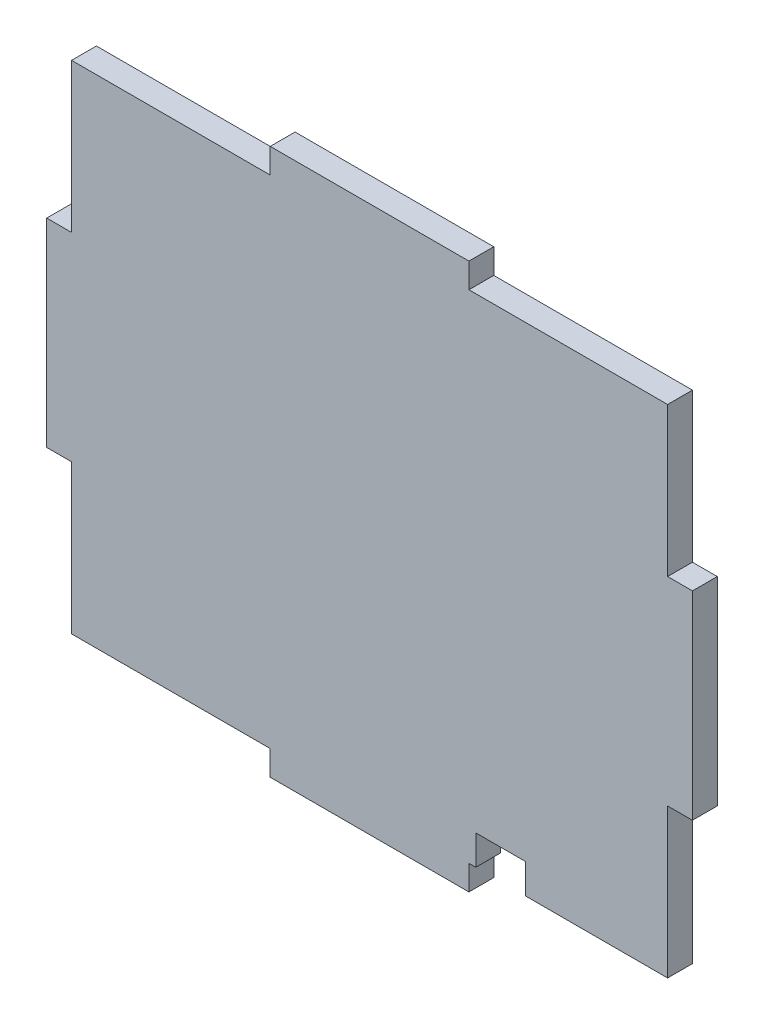
SolidWorks part; units mm, degrees
material "Maple"
ref_plane "Front Plane" through (0, 0, 0) normal (0, 0, 1) x (1, 0, 0)
ref_plane "Top Plane" through (0, 0, 0) normal (0, 1, 0) x (1, 0, 0)
ref_plane "Right Plane" through (0, 0, 0) normal (1, 0, 0) x (0, 0, -1)
sketch "Sketch1" plane through (0, 0, 0) normal (0, 0, 1) x (1, 0, 0)
  line L0 (-30, -25) -> (-30, 25) construction
  line L1 (-32.5, -27.5) -> (32.5, -27.5) construction
  line L2 (-32.5, -27.5) -> (-32.5, 27.5) construction
  line L3 (-32.5, 27.5) -> (32.5, 27.5) construction
  line L4 (32.5, -27.5) -> (32.5, 27.5) construction
  line L5 (-32.5, -27.5) -> (32.5, 27.5) construction
  line L6 (-32.5, 27.5) -> (32.5, -27.5) construction
  line L7 (-30, 25) -> (30, 25) construction
  line L8 (30, -25) -> (30, 25) construction
  line L9 (-30, -25) -> (30, -25) construction
  line L10 (-32.5, 10) -> (-32.5, -10)
  line L11 (-32.5, -10) -> (-30, -10)
  line L12 (-30, -10) -> (-30, -25)
  line L13 (-30, -25) -> (-10, -25)
  line L14 (-10, -25) -> (-10, -27.5)
  line L15 (-10, -27.5) -> (10, -27.5)
  line L16 (-9.4058, 0) -> (8.9806, 0) construction
  line L17 (0, -5.5705) -> (0, 7.9444) construction
  line L18 (-10, 27.5) -> (10, 27.5)
  line L19 (-10, 25) -> (-10, 27.5)
  line L20 (-30, 25) -> (-10, 25)
  line L21 (-30, 10) -> (-30, 25)
  line L22 (-32.5, 10) -> (-30, 10)
  line L23 (10, -25) -> (10, -27.5)
  line L24 (30, -25) -> (10, -25)
  line L25 (30, -10) -> (30, -25)
  line L26 (32.5, -10) -> (30, -10)
  line L27 (32.5, 10) -> (32.5, -10)
  line L28 (32.5, 10) -> (30, 10)
  line L29 (30, 10) -> (30, 25)
  line L30 (30, 25) -> (10, 25)
  line L31 (10, 25) -> (10, 27.5)
  line L32 (10.69, -25) -> (10.69, -22)
  line L33 (10.69, -22) -> (15.69, -22)
  line L34 (15.69, -22) -> (15.69, -25)
  point P0 (0, 0)
  point P25 (-32.5, 0)
  point P26 (0, -27.5)
  point P33 (0, 27.5)
  point P35 (11.0862, -25)
  point P38 (11.0035, -25)
  point P39 (10.6328, -25)
  point P41 (16.0965, -25)
  point P42 (0, 0)
  point P43 (15.7267, -25)
  dimension "D1" = 65
  dimension "D2" = 55
  dimension "D4" = 20
  dimension "D5" = 5
  dimension "D6" = 3
  dimension "D7" = 0.69
  dimension "D3" = 2.5
extrude "Boss-Extrude1" add sketch "Sketch1" along normal mid plane 2.5 contours L33 L34 L24 L25 L26 L27 L28 L29 L30 L31 L18 L19 L20 L21 L22 L10 L11 L12 L13 L14 L15 L23 L32
